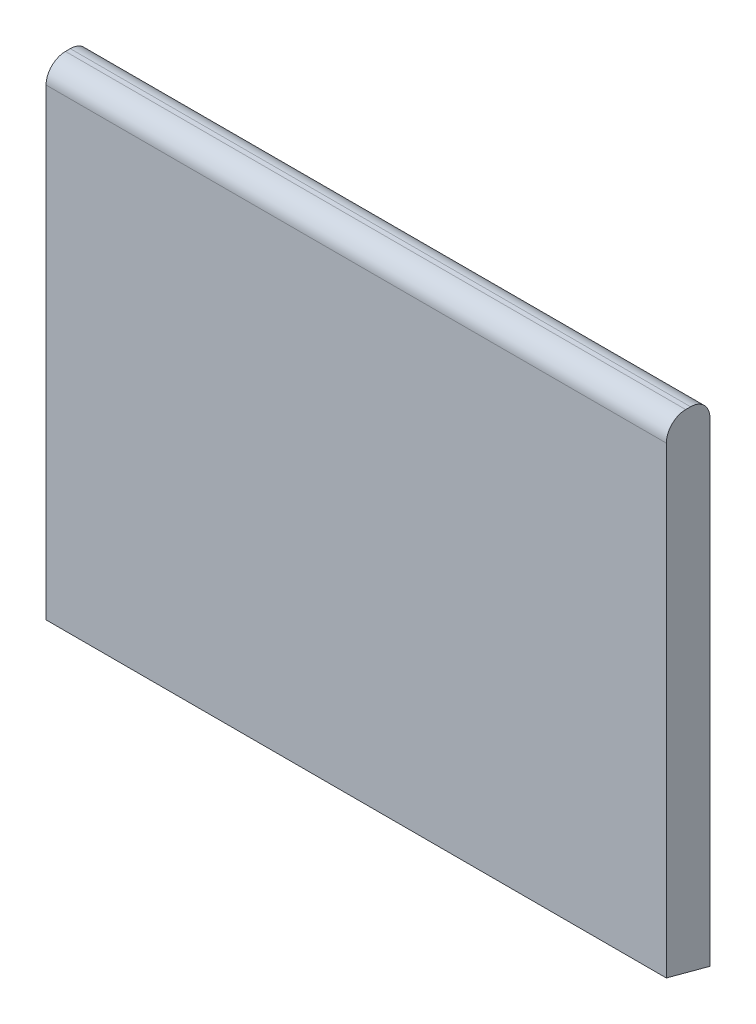
SolidWorks part; units mm, degrees
ref_plane "Plan de face" through (0, 0, 0) normal (0, 0, 1) x (1, 0, 0)
ref_plane "Plan de dessus" through (0, 0, 0) normal (0, 1, 0) x (1, 0, 0)
ref_plane "Plan de droite" through (0, 0, 0) normal (1, 0, 0) x (0, 0, -1)
sketch "Esquisse1" plane through (0, 0, 0) normal (0, 0, 1) x (1, 0, 0)
  line L1 (0, 0) -> (256, 0)
  line L2 (0, 0) -> (0, 204)
  line L3 (0, 204) -> (256, 204)
  line L4 (256, 0) -> (256, 204)
  dimension "D1" = 204
  dimension "D2" = 256
extrude "Boss.-Extru.1" add sketch "Esquisse1" along normal blind 18
fillet "Congé1" radius 8 2 edges at (128, 204, 18) (128, 204, 0)
sketch "Esquisse4" plane through (256, 0, 0) normal (1, 0, 0) x (0, 0, -1)
  line L0 (0, 0) -> (-18, 0)
  line L1 (-18, 0) -> (-18, 4.8231)
  line L2 (-18, 0) -> (-18, 196) construction
  line L3 (-18, 4.8231) -> (0, 0)
  dimension "D1" = 15
extrude "Enlèv. mat.-Extru.2" cut sketch "Esquisse4" against normal through all both and the other way through all
